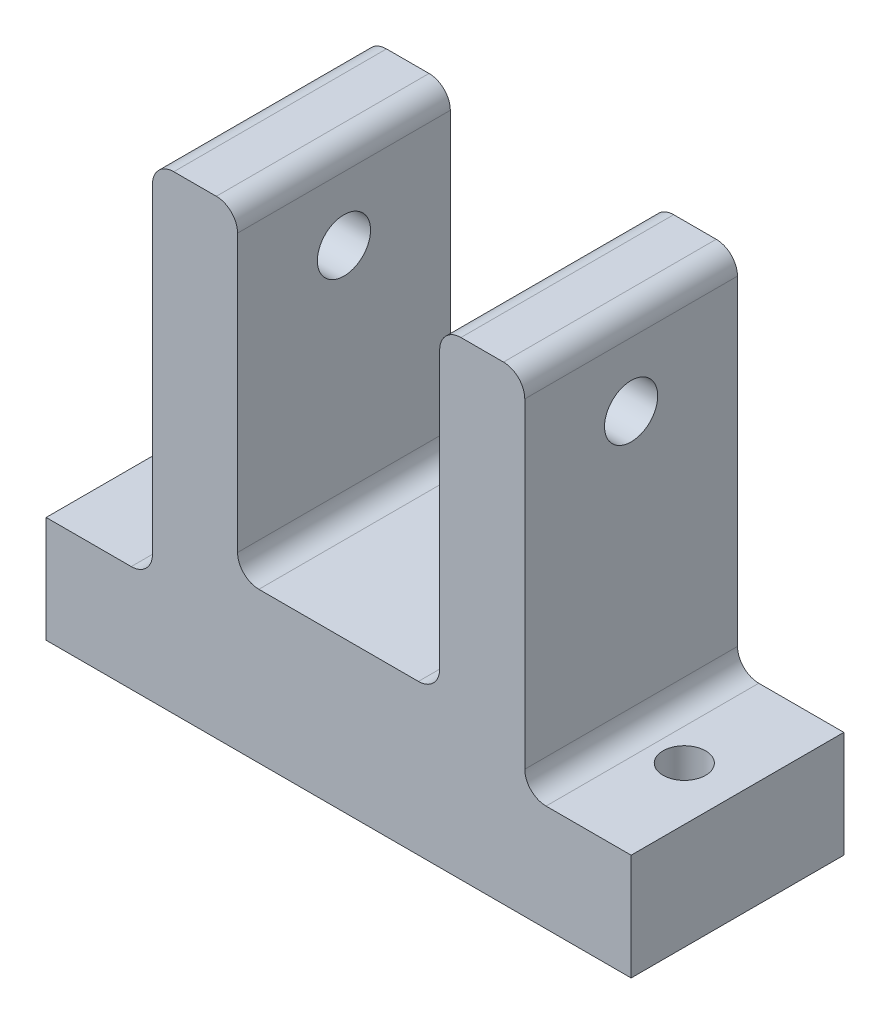
SolidWorks part; units mm, degrees
ref_plane "Front Plane" through (0, 0, 0) normal (0, 0, 1) x (1, 0, 0)
ref_plane "Top Plane" through (0, 0, 0) normal (0, 1, 0) x (1, 0, 0)
ref_plane "Right Plane" through (0, 0, 0) normal (1, 0, 0) x (0, 0, -1)
sketch "Sketch1" plane through (0, 0, 0) normal (0, 1, 0) x (1, 0, 0)
  line L1 (-17.5, -10) -> (17.5, -10)
  line L2 (-17.5, -10) -> (-17.5, 10)
  line L3 (-17.5, 10) -> (17.5, 10)
  line L4 (17.5, -10) -> (17.5, 10)
  line L5 (-17.5, -10) -> (17.5, 10) construction
  line L6 (-17.5, 10) -> (17.5, -10) construction
  point P0 (0, 0)
  dimension "D1" = 20
  dimension "D2" = 35
extrude "Boss-Extrude1" add sketch "Sketch1" along normal blind 44.15
sketch "Sketch2" plane through (0, 44.15, 0) normal (0, 1, 0) x (1, 0, 0)
  line L0 (17.5, 10) -> (-17.5, 10) construction
  line L1 (-9.5, -10) -> (9.5, -10)
  line L2 (-9.5, -10) -> (-9.5, 10)
  line L3 (-9.5, 10) -> (9.5, 10)
  line L4 (9.5, -10) -> (9.5, 10)
  line L5 (-9.5, -10) -> (9.5, 10) construction
  line L6 (-9.5, 10) -> (9.5, -10) construction
  line L7 (17.5, -10) -> (17.5, 10) construction
  point P0 (0, 0)
  dimension "D1" = 8
extrude "Cut-Extrude1" cut sketch "Sketch2" against normal blind 30
sketch "Sketch3" plane through (17.5, 0, 0) normal (1, 0, 0) x (0, 0, -1)
  line L0 (-10, 0) -> (10, 0) construction
  circle A0 centre (0, 36.15) radius 2.5
  dimension "D2" = 5
  dimension "D1" = 36.15
extrude "Cut-Extrude2" cut sketch "Sketch3" against normal through all both and the other way through all
fillet "Fillet1" radius 2 4 edges at (9.5, 14.15, 0) (-9.5, 14.15, 0) (9.5, 44.15, 0) (-9.5, 44.15, 0)
sketch "Sketch4" plane through (0, 0, 0) normal (0, -1, 0) x (1, 0, 0)
  line L0 (17.5, -10) -> (-17.5, -10) construction
  line L1 (17.5, 10) -> (27.5, 10)
  line L2 (17.5, 10) -> (17.5, -10)
  line L3 (17.5, -10) -> (27.5, -10)
  line L4 (27.5, 10) -> (27.5, -10)
  line L6 (0, -11) -> (0, 11) construction
  line L7 (-27.5, 10) -> (-27.5, -10)
  line L8 (-17.5, -10) -> (-27.5, -10)
  line L9 (-17.5, 10) -> (-17.5, -10)
  line L10 (-17.5, 10) -> (-27.5, 10)
  circle A0 centre (22.5, 0) radius 2
  circle A1 centre (-22.5, 0) radius 2
  point P10 (22.5, 10)
  dimension "D2" = 4
  dimension "D1" = 10
extrude "Boss-Extrude2" add sketch "Sketch4" against normal blind 10
fillet "Fillet2" radius 2 4 edges at (17.5, 10, 0) (-17.5, 10, 0) (17.5, 44.15, 0) (-17.5, 44.15, 0)
